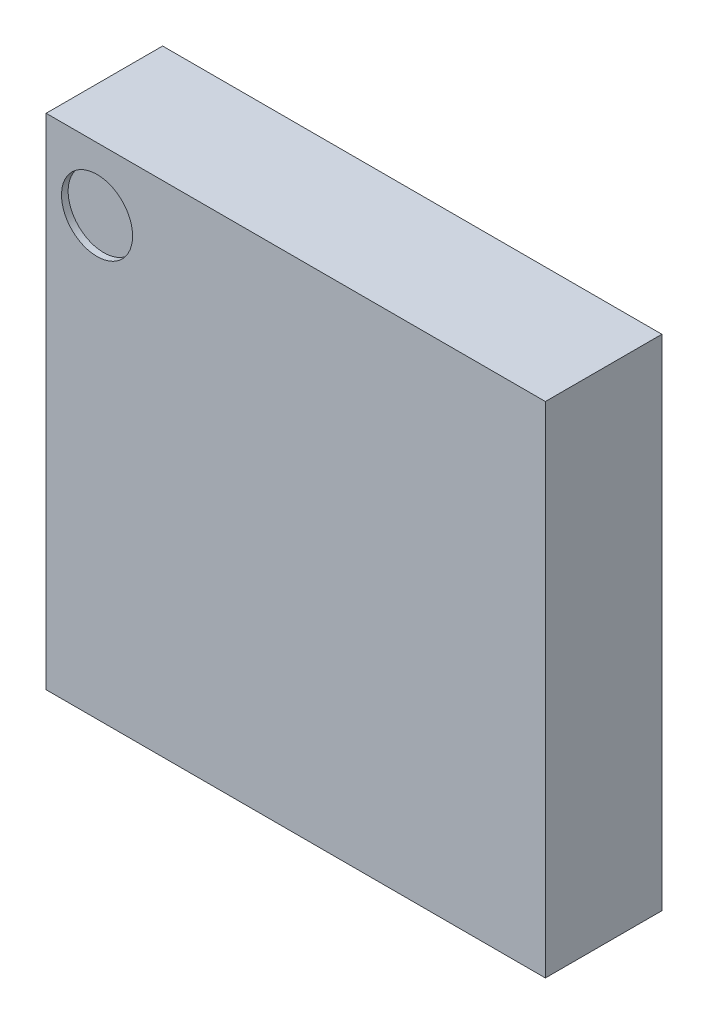
SolidWorks part; units mm, degrees
ref_plane "Front Plane" through (0, 0, 0) normal (0, 0, 1) x (1, 0, 0)
ref_plane "Top Plane" through (0, 0, 0) normal (0, 1, 0) x (1, 0, 0)
ref_plane "Right Plane" through (0, 0, 0) normal (1, 0, 0) x (0, 0, -1)
sketch "Sketch1" plane through (0, 0, 0) normal (0, 0, 1) x (1, 0, 0)
  line L1 (-0.75, -0.75) -> (0.75, -0.75)
  line L2 (-0.75, -0.75) -> (-0.75, 0.75)
  line L3 (-0.75, 0.75) -> (0.75, 0.75)
  line L4 (0.75, -0.75) -> (0.75, 0.75)
  line L5 (-0.75, -0.75) -> (0.75, 0.75) construction
  line L6 (-0.75, 0.75) -> (0.75, -0.75) construction
  point P0 (0, 0)
  dimension "D1" = 1.5
  dimension "D2" = 1.5
extrude "Boss-Extrude1" add sketch "Sketch1" along normal blind 0.35 from offset 0.1 contours L4 L3 L2 L1
ref_plane "Plane1" through (0, -0.525, 0) normal (0, -1, 0) x (-1, 0, 0)
sketch "Sketch4" plane through (0, -0.525, 0) normal (0, -1, 0) x (-1, 0, 0)
  line L0 (0.525, -0.17) -> (0.525, 0.05)
  line L1 (0.75, -0.1) -> (-0.75, -0.1) construction
  arc A0 (0.525, 0.05) -> (0.525, -0.17) centre (0.525, -0.06) cw
  dimension "D1" = 0.22
  dimension "D2" = 0.15
  dimension "D3" = 0.225
revolve "Revolve2" add sketch "Sketch4" angle 360 about L0
pattern_linear "LPattern2" count 4 spacing 0.35 along (1, 0, 0) count 4 spacing 0.35 along (0, 1, 0) of "Revolve2"
sketch "Sketch3" plane through (0, 0, 0.45) normal (0, 0, 1) x (1, 0, 0)
  circle A0 centre (-0.597, 0.5606) radius 0.1068
  point P2 (-3.6411, 6.6615)
  point P3 (-0.3815, 0.2953)
  point P4 (-0.597, 0.5606)
extrude "Cut-Extrude1" cut sketch "Sketch3" against normal blind 0.02
